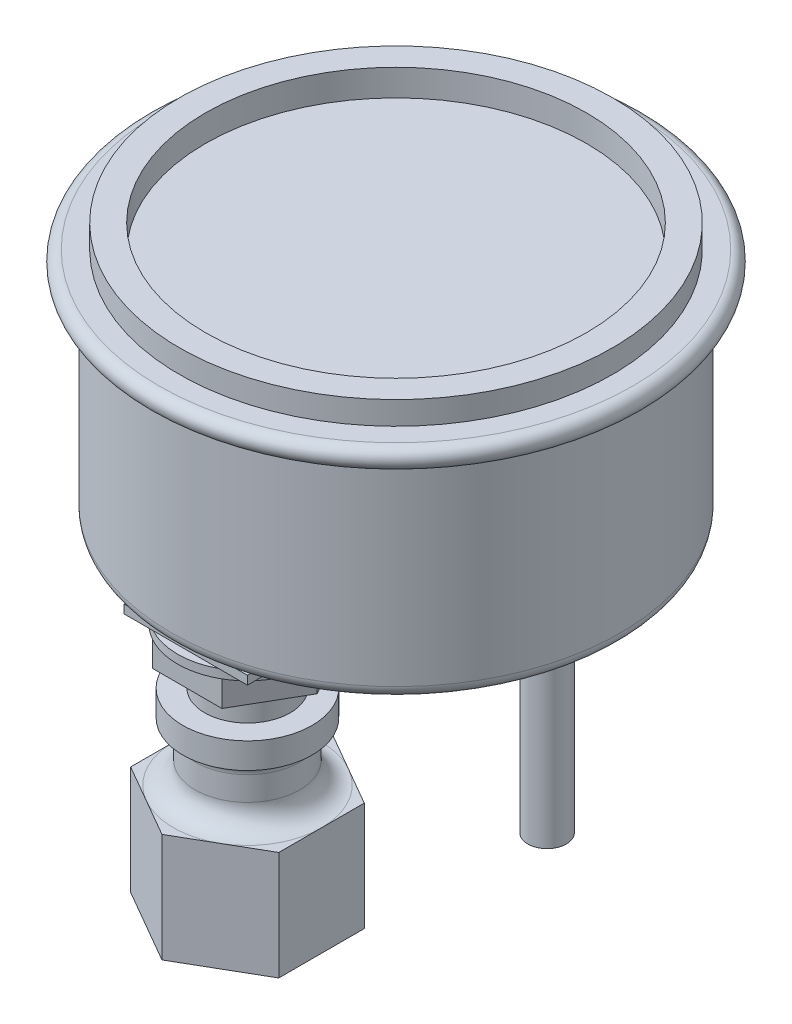
SolidWorks part; units mm, degrees
ref_plane "Front Plane" through (0, 0, 0) normal (0, 0, 1) x (1, 0, 0)
ref_plane "Top Plane" through (0, 0, 0) normal (0, 1, 0) x (1, 0, 0)
ref_plane "Right Plane" through (0, 0, 0) normal (1, 0, 0) x (0, 0, -1)
sketch "Sketch1" plane through (0, 0, 0) normal (0, 0, 1) x (1, 0, 0)
  line L0 (0, 0) -> (0, 26.8)
  line L1 (0, 26.8) -> (22.25, 26.8)
  line L2 (22.25, 26.8) -> (22.25, 29.9)
  line L3 (22.25, 29.9) -> (25.3, 29.9)
  line L4 (25.3, 29.9) -> (25.3, 27.2)
  line L5 (25.3, 27.2) -> (27.65, 27.2)
  line L6 (27.65, 24.8) -> (26.2, 24.8)
  line L7 (26.2, 24.8) -> (26.2, 1.5)
  line L8 (24.7, 0) -> (0, 0)
  line L9 (0, -4.0696) -> (0, 24.0575) construction
  arc A0 (27.65, 27.2) -> (27.65, 24.8) centre (27.65, 26) cw
  arc A1 (26.2, 1.5) -> (24.7, 0) centre (24.7, 1.5) cw
  point P15 (28.85, 26)
  dimension "D4" = 1.2
  dimension "D9" = 1.5
  dimension "D1" = 44.5
  dimension "D2" = 50.6
  dimension "D3" = 57.7
  dimension "D5" = 3.1
  dimension "D6" = 2.7
  dimension "D7" = 29.9
  dimension "D8" = 52.4
revolve "Revolve1" add sketch "Sketch1" angle 360 about L9
sketch "Sketch2" plane through (0, 0, 0) normal (0, -1, 0) x (1, 0, 0)
  line L0 (0, 0) -> (-17.65, 0) construction
  line L1 (0, 0) -> (0, -17.65) construction
  circle A2 centre (-17.65, 0) radius 4.3
  circle A3 centre (0, -17.65) radius 4.3
  circle A4 centre (17.65, 0) radius 4.3
  point P1 (-21.95, 0)
  point P2 (21.95, 0)
  point P11 (0, 0)
  point P13 (6.9056, -16.5354)
  dimension "D1" = 8.6
  dimension "D3" = 43.9
  dimension "D2" = 3
extrude "Boss-Extrude1" add sketch "Sketch2" along normal blind 1.8
sketch "Sketch3" plane through (0, -1.8, 0) normal (0, -1, 0) x (1, 0, 0)
  circle A0 centre (-17.65, 0) radius 2.25
  circle A1 centre (17.65, 0) radius 2.25
  dimension "D1" = 4.5
extrude "Boss-Extrude2" add sketch "Sketch3" along normal blind 21.2
sketch "Sketch4" plane through (0, -1.8, 0) normal (0, -1, 0) x (1, 0, 0)
  circle A0 centre (0, -17.65) radius 2.25
  circle A1 centre (-17.65, 0) radius 2.25 construction
extrude "Boss-Extrude3" add sketch "Sketch4" along normal blind 14.8
sketch "Sketch5" plane through (0, 0, 0) normal (0, -1, 0) x (1, 0, 0)
  line L1 (-7.2, 10.15) -> (7.2, 10.15)
  line L2 (-7.2, 10.15) -> (-7.2, 24.55)
  line L3 (-7.2, 24.55) -> (7.2, 24.55)
  line L4 (7.2, 10.15) -> (7.2, 24.55)
  line L5 (-7.2, 10.15) -> (7.2, 24.55) construction
  line L6 (-7.2, 24.55) -> (7.2, 10.15) construction
  circle A0 centre (0, -17.65) radius 4.3 construction
  circle A1 centre (0, -17.65) radius 4.3 construction
  point P0 (0, 17.35)
  point P5 (0, 17.35)
  point P7 (0, -21.95)
  point P8 (7.2, 10.15)
  point P13 (0, 0)
  dimension "D1" = 14.4
  dimension "D2" = 46.5
extrude "Boss-Extrude4" add sketch "Sketch5" along normal blind 1
sketch "Sketch6" plane through (0, -1, 0) normal (0, -1, 0) x (1, 0, 0)
  line L0 (7.2, 10.15) -> (-7.2, 24.55) construction
  circle A0 centre (0, 17.35) radius 8.15
  dimension "D1" = 16.3
extrude "Boss-Extrude5" add sketch "Sketch6" along normal blind 1
sketch "Sketch7" plane through (0, -2, 0) normal (0, -1, 0) x (1, 0, 0)
  line L1 (8.1406, 17.35) -> (4.0703, 24.4)
  line L2 (4.0703, 24.4) -> (-4.0703, 24.4)
  line L3 (-4.0703, 24.4) -> (-8.1406, 17.35)
  line L4 (-8.1406, 17.35) -> (-4.0703, 10.3)
  line L5 (-4.0703, 10.3) -> (4.0703, 10.3)
  line L6 (4.0703, 10.3) -> (8.1406, 17.35)
  circle A0 centre (0, 17.35) radius 7.05 construction
  dimension "D1" = 14.1
extrude "Boss-Extrude6" add sketch "Sketch7" along normal blind 3
ref_plane "Plane1" through (7.5128, 0, 4.3375) normal (0.866, 0, 0.5) x (0.5, 0, -0.866)
sketch "Sketch8" plane through (7.5128, 0, 4.3375) normal (0.866, 0, 0.5) x (0.5, 0, -0.866)
  line L0 (-15.0255, -16.5842) -> (-15.0255, -6.9426) construction
  line L1 (-10.9552, -5) -> (-19.0959, -5) construction
  line L2 (-20.0255, -5) -> (-20.0255, -8.5)
  line L3 (-20.0255, -8.5) -> (-22.5755, -8.5)
  line L4 (-22.5755, -8.5) -> (-22.5755, -11.5)
  line L5 (-21.1255, -12.95) -> (-21.1255, -15.75)
  line L6 (-23.6755, -18.3) -> (-15.0255, -18.3)
  line L7 (-15.0255, -18.3) -> (-15.0255, -5)
  line L8 (-15.0255, -5) -> (-20.0255, -5)
  line L9 (-23.0036, -11.5) -> (-28.7744, -11.5) construction
  line L10 (-24.7, 0) -> (24.7, 0) construction
  arc A0 (-22.5755, -11.5) -> (-21.1255, -12.95) centre (-22.5755, -12.95) cw
  arc A1 (-21.1255, -15.75) -> (-23.6755, -18.3) centre (-23.6755, -15.75) cw
  point P4 (-15.0255, -5)
  dimension "D1" = 3.5
  dimension "D2" = 10
  dimension "D3" = 15.1
  dimension "D4" = 3
  dimension "D5" = 12.2
  dimension "D6" = 17.3
  dimension "D7" = 18.3
revolve "Revolve2" add sketch "Sketch8" angle 360 about L0
sketch "Sketch9" plane through (0, -18.3, 0) normal (0, -1, 0) x (1, 0, 0)
  line L1 (0, 27.3382) -> (-8.65, 22.3441)
  line L2 (-8.65, 22.3441) -> (-8.65, 12.3559)
  line L3 (-8.65, 12.3559) -> (0, 7.3618)
  line L4 (0, 7.3618) -> (8.65, 12.3559)
  line L5 (8.65, 12.3559) -> (8.65, 22.3441)
  line L6 (8.65, 22.3441) -> (0, 27.3382)
  circle A0 centre (0, 17.35) radius 8.65 construction
  circle A1 centre (0, 17.35) radius 5.6
  dimension "D2" = 11.2
  dimension "D1" = 17.3
extrude "Boss-Extrude7" add sketch "Sketch9" along normal blind 12.7
